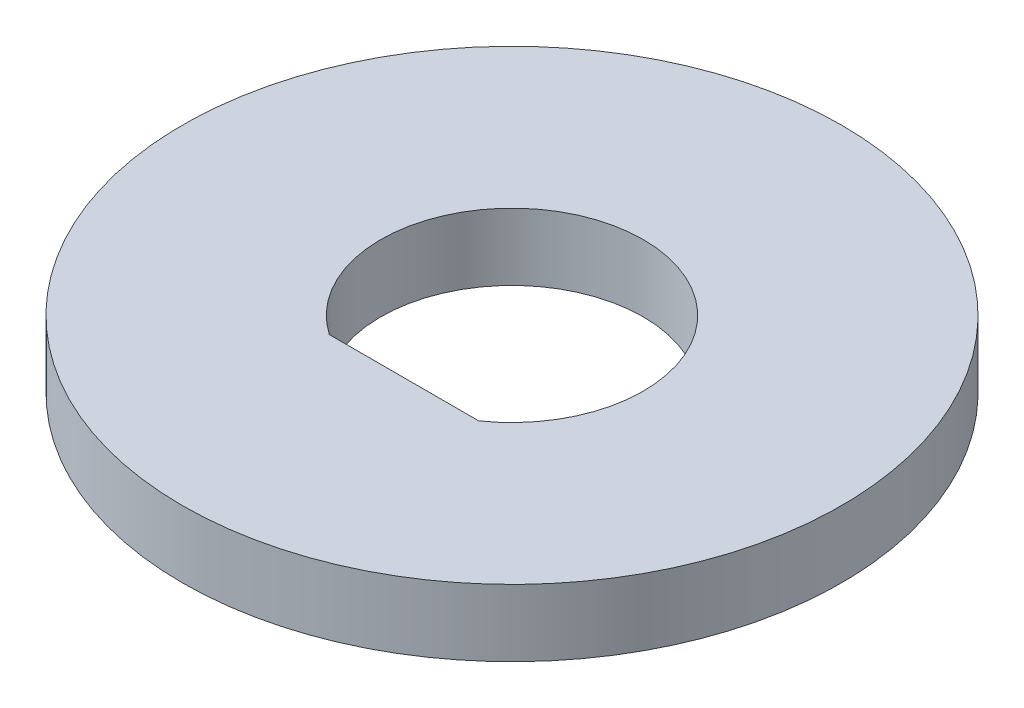
SolidWorks part; units mm, degrees
ref_plane "前视基准面" through (0, 0, 0) normal (0, 0, 1) x (1, 0, 0)
ref_plane "上视基准面" through (0, 0, 0) normal (0, 1, 0) x (1, 0, 0)
ref_plane "右视基准面" through (0, 0, 0) normal (1, 0, 0) x (0, 0, -1)
other "Configuration Table"
sketch "草图1" plane through (0, 0, 0) normal (0, 1, 0) x (1, 0, 0)
  line L0 (-2.9, -4.1952) -> (2.9, -4.1952)
  line L1 (0, 0) -> (0, -4.1952) construction
  circle A0 centre (0, 0) radius 12.8
  arc A1 (2.9, -4.1952) -> (-2.9, -4.1952) centre (0, 0) ccw
  point P6 (3.4163, -3.7867)
  dimension "D1" = 5.1
  dimension "D3" = 25.6
  dimension "D2" = 5.8
extrude "凸台-拉伸1" add sketch "草图1" along normal blind 2.6
